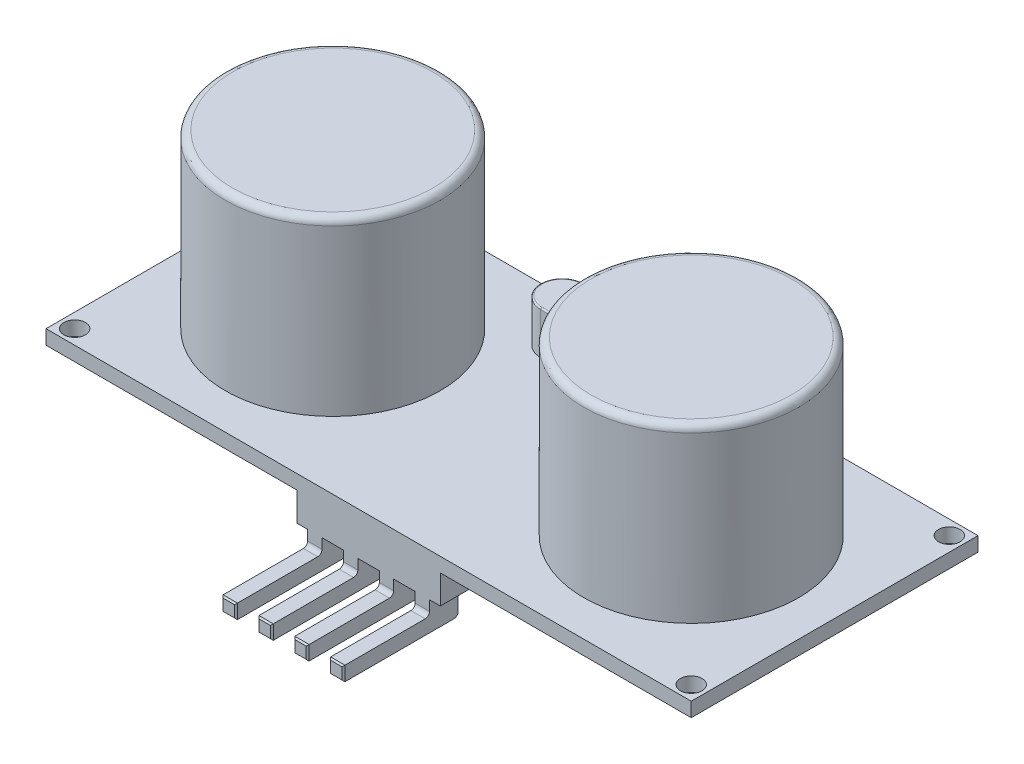
SolidWorks part; units mm, degrees
ref_plane "Plan de face" through (0, 0, 0) normal (0, 0, 1) x (1, 0, 0)
ref_plane "Plan de dessus" through (0, 0, 0) normal (0, 1, 0) x (1, 0, 0)
ref_plane "Plan de droite" through (0, 0, 0) normal (1, 0, 0) x (0, 0, -1)
sketch "Esquisse1" plane through (0, 0, 0) normal (0, 1, 0) x (1, 0, 0)
  line L1 (-22.5, -10) -> (22.5, -10)
  line L2 (-22.5, -10) -> (-22.5, 10)
  line L3 (-22.5, 10) -> (22.5, 10)
  line L4 (22.5, -10) -> (22.5, 10)
  line L5 (-22.5, -10) -> (22.5, 10) construction
  line L6 (-22.5, 10) -> (22.5, -10) construction
  point P0 (0, 0)
  dimension "D1" = 20
  dimension "D2" = 45
extrude "Boss.-Extru.1" add sketch "Esquisse1" along normal blind 1
sketch "Esquisse2" plane through (0, 1, 0) normal (0, 1, 0) x (1, 0, 0)
  line L0 (22.5, 10) -> (-22.5, 10) construction
  line L1 (-22.5, 10) -> (-22.5, -10) construction
  circle A0 centre (-21.5, 9) radius 0.75
  dimension "D1" = 1
  dimension "D3" = 1.5
  dimension "D2" = 1
extrude "Enlèv. mat.-Extru.1" cut sketch "Esquisse2" against normal up to next
mirror "Symétrie1" about plane through (0, 0, 0) normal (1, 0, 0) of "Enlèv. mat.-Extru.1"
mirror "Symétrie2" about plane through (0, 0, 0) normal (0, 0, 1) of "Symétrie1", "Enlèv. mat.-Extru.1"
sketch "Esquisse3" plane through (0, 1, 0) normal (0, 1, 0) x (1, 0, 0)
  line L0 (-12.5, 0) -> (12.5, 0) construction
  circle A0 centre (-12.5, 0) radius 7.5
  circle A1 centre (12.5, 0) radius 7.5
  point P4 (14.5637, 0)
  point P6 (0, 0)
  dimension "D1" = 15
  dimension "D2" = 25
extrude "Boss.-Extru.2" add sketch "Esquisse3" along normal blind 12
fillet "Congé1" radius 0.5 2 edges at (-12.5, 13, 7.5) (12.5, 13, 7.5)
sketch "Esquisse4" plane through (0, 1, 0) normal (0, 1, 0) x (1, 0, 0)
  line L0 (-3.5, 7) -> (3.5, 7) construction
  line L1 (-3.5, 8.5) -> (3.5, 8.5)
  line L2 (-3.5, 5.5) -> (3.5, 5.5)
  line L3 (22.5, 10) -> (-22.5, 10) construction
  arc A0 (-3.5, 8.5) -> (-3.5, 5.5) centre (-3.5, 7) ccw
  arc A1 (3.5, 5.5) -> (3.5, 8.5) centre (3.5, 7) ccw
  point P2 (0, 7)
  dimension "D1" = 3
  dimension "D2" = 7
  dimension "D3" = 3
extrude "Boss.-Extru.3" add sketch "Esquisse4" along normal blind 3
fillet "Congé2" radius 0.1 4 edges at (0, 4, -8.5) (5, 4, -7) (0, 4, -5.5) (-5, 4, -7)
sketch "Esquisse5" plane through (0, 0, 0) normal (0, -1, 0) x (1, 0, 0)
  line L0 (-22.5, 10) -> (22.5, 10) construction
  line L1 (-5, 10) -> (5, 10)
  line L2 (-5, 10) -> (-5, 8)
  line L3 (-5, 8) -> (5, 8)
  line L4 (5, 10) -> (5, 8)
  point P6 (0, 8)
  dimension "D1" = 2
  dimension "D2" = 10
extrude "Boss.-Extru.4" add sketch "Esquisse5" along normal blind 4
sketch "Esquisse6" plane through (0, 0, 10) normal (0, 0, 1) x (1, 0, 0)
  line L0 (5, -4) -> (5, 0) construction
  line L1 (-5, -4) -> (5, -4)
  line L2 (-5, -4) -> (-5, -3)
  line L3 (-5, -3) -> (5, -3)
  line L4 (5, -4) -> (5, -3)
  dimension "D1" = 1
extrude "Boss.-Extru.5" add sketch "Esquisse6" along normal blind 6
sketch "Esquisse7" plane through (0, 0, 8) normal (0, 0, -1) x (-1, 0, 0)
  line L0 (5, -4) -> (-5, -4) construction
  line L1 (-3.25, -4) -> (-1.75, -4)
  line L2 (-3.25, -4) -> (-3.25, -2)
  line L3 (-3.25, -2) -> (-1.75, -2)
  line L4 (-1.75, -4) -> (-1.75, -2)
  line L5 (-5, -4) -> (-5, 0) construction
  line L6 (-5, -2) -> (-4.25, -2)
  line L7 (-5, -2) -> (-5, -4)
  line L8 (-5, -4) -> (-4.25, -4)
  line L9 (-4.25, -2) -> (-4.25, -4)
  line L10 (5, -4) -> (5, 0) construction
  line L11 (-0.75, -2) -> (0.75, -2)
  line L12 (-0.75, -2) -> (-0.75, -4)
  line L13 (-0.75, -4) -> (0.75, -4)
  line L14 (0.75, -2) -> (0.75, -4)
  line L15 (1.75, -2) -> (3.25, -2)
  line L16 (1.75, -2) -> (1.75, -4)
  line L17 (1.75, -4) -> (3.25, -4)
  line L18 (3.25, -2) -> (3.25, -4)
  line L19 (4.25, -2) -> (5, -2)
  line L20 (4.25, -2) -> (4.25, -4)
  line L21 (4.25, -4) -> (5, -4)
  line L22 (5, -2) -> (5, -4)
  line L23 (-22.5, 0) -> (22.5, 0) construction
  point P28 (-7.831, -1.2983)
  dimension "D1" = 1.5
  dimension "D2" = 1
  dimension "D3" = 1
  dimension "D4" = 1
  dimension "D5" = 2
  dimension "D6" = 1
extrude "Enlèv. mat.-Extru.2" cut sketch "Esquisse7" against normal up to next
chamfer "Chanfrein1" distance 0.1 angle 45 16 edges at (4.25, -3.5, 16) (3.75, -3, 16) (3.25, -3.5, 16) (3.75, -4, 16) (1.25, -3, 16) (1.75, -3.5, 16) (1.25, -4, 16) (0.75, -3.5, 16) (-1.25, -3, 16) (-0.75, -3.5, 16) (-1.25, -4, 16) (-1.75, -3.5, 16) (-3.25, -3.5, 16) (-3.75, -3, 16) (-4.25, -3.5, 16) (-3.75, -4, 16)
fillet "Congé3" radius 0.3 8 edges at (-3.75, -3, 10) (-1.25, -3, 10) (1.25, -3, 10) (3.75, -3, 10) (-3.75, -4, 8) (-1.25, -4, 8) (1.25, -4, 8) (3.75, -4, 8)
equation "\"éà\"=60.5356"
